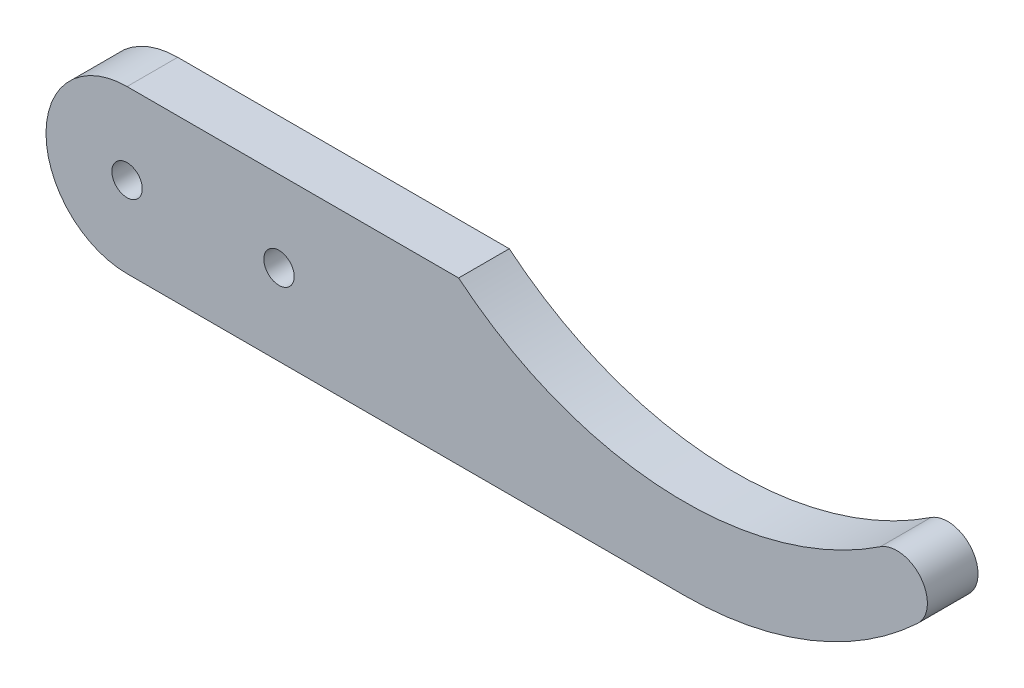
SolidWorks part; units mm, degrees
ref_plane "Plan de face" through (0, 0, 0) normal (0, 0, 1) x (1, 0, 0)
ref_plane "Plan de dessus" through (0, 0, 0) normal (0, 1, 0) x (1, 0, 0)
ref_plane "Plan de droite" through (0, 0, 0) normal (1, 0, 0) x (0, 0, -1)
sketch "Esquisse1" plane through (0, 0, 0) normal (0, 0, 1) x (1, 0, 0)
  line L0 (0, 0) -> (80, 0) construction
  line L2 (0, 0) -> (0, 35) construction
  line L3 (0, 35) -> (40, 35) construction
  line L4 (0, 8) -> (17.7289, 8)
  line L5 (59.3421, 5.8301) -> (61, 3.3298) construction
  line L7 (0, -8) -> (40, -8)
  line L8 (40, 35) -> (40, -8) construction
  line L9 (0, 8) -> (-15, 8)
  line L10 (0, 0) -> (-15, 0) construction
  line L11 (0, -8) -> (-15, -8)
  circle A0 centre (0, 0) radius 1.5
  arc A1 (0, -8) -> (0, 8) centre (0, 0) cw construction
  circle A2 centre (40, 35) radius 35 construction
  arc A3 (17.7289, 8) -> (59.3421, 5.8301) centre (40, 35) ccw
  arc A4 (59.3421, 5.8301) -> (63.0564, 1.1455) centre (61, 3.3298) cw
  arc A5 (40, -8) -> (63.0564, 1.1455) centre (40, 25.6361) ccw
  circle A6 centre (15, 0) radius 1.5 construction
  arc A7 (-15, 8) -> (-15, -8) centre (-15, 0) ccw
  circle A8 centre (-15, 0) radius 1.5
  dimension "D3" = 3
  dimension "D4" = 35
  dimension "D6" = 70
  dimension "D7" = 3
  dimension "D8" = 8
  dimension "D9" = 21
  dimension "D10" = 15
  dimension "D11" = 8
  dimension "D2" = 80
  dimension "D5" = 40
  dimension "D12" = 15
extrude "Boss.-Extru.1" add sketch "Esquisse1" along normal blind 5
